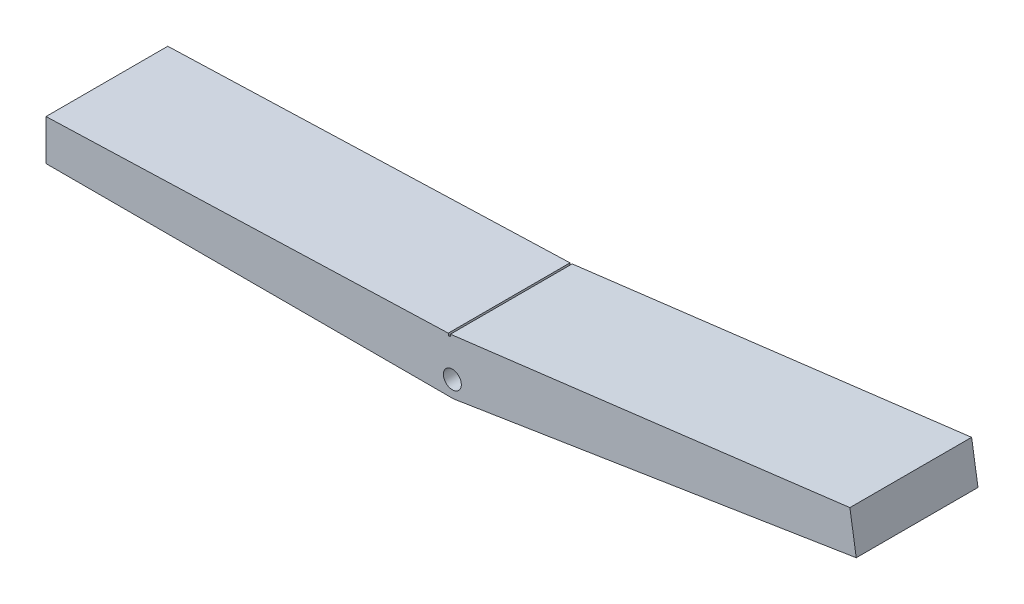
SolidWorks part; units mm, degrees
ref_plane "Front Plane" through (0, 0, 0) normal (0, 0, 1) x (1, 0, 0)
ref_plane "Top Plane" through (0, 0, 0) normal (0, 1, 0) x (1, 0, 0)
ref_plane "Right Plane" through (0, 0, 0) normal (1, 0, 0) x (0, 0, -1)
sketch "Sketch1" plane through (0, 0, 0) normal (0, 0, 1) x (1, 0, 0)
  line L1 (0, 0) -> (-75, 0)
  line L4 (-75, 0) -> (-75, 7.5)
  line L5 (0, 0) -> (5, 0) construction
  line L6 (0, 0) -> (74.0766, 11.7326)
  line L7 (74.0766, 11.7326) -> (72.9034, 19.1402)
  line L9 (74.0766, 0) -> (74.0766, 11.7326) construction
  line L10 (74.0766, 0) -> (0, 0) construction
  line L11 (-0.787, 10) -> (0, 0) construction
  line L12 (-0.787, 10) -> (-75, 7.5)
  line L13 (-0.787, 10) -> (72.9034, 19.1402)
  circle A0 centre (-0.2354, 2.9908) radius 1.65
  dimension "D8" = 3.3
  dimension "D3" = 75
  dimension "D4" = 75
  dimension "D5" = 5
  dimension "D7" = 3
  dimension "D6" = 9
  dimension "D9" = 85.5
extrude "Boss-Extrude1" add sketch "Sketch1" along normal blind 22.4 contours L4 L12 L13 L7 L6 L1 | A0
sketch "Sketch2" plane through (0, 0, 0) normal (0.1564, -0.9877, 0) x (0.9877, 0.1564, 0)
  line L0 (67, 7.7) -> (67, 14.7) construction
  line L1 (67, 11.2) -> (75, 11.2) construction
  line L2 (75, 22.4) -> (75, 0) construction
  circle A0 centre (67, 14.7) radius 3.05
  circle A1 centre (67, 7.7) radius 3.05
  dimension "D1" = 6.1
  dimension "D2" = 7
  dimension "D3" = 8
extrude "Cut-Extrude1" cut sketch "Sketch2" against normal blind 3
ref_plane "Plane1" through (0, 0, 0) normal (0.9969, 0.0785, 0) x (0, 0, -1)
mirror "Mirror1" about plane through (0, 0, 0) normal (0.9969, 0.0785, 0) of "Cut-Extrude1"
ref_plane "Plane2" through (-1.0483, 13.3201, 0) normal (-0.0785, 0.9969, 0) x (0.9969, 0.0785, 0)
sketch "Sketch3" plane through (-1.0483, 13.3201, 0) normal (-0.0785, 0.9969, 0) x (0.9969, 0.0785, 0)
  line L0 (0, 0) -> (74.1804, 0) construction
  line L1 (-0.2, 0) -> (0.2, 0)
  line L2 (-0.2, 0) -> (-0.2, -22.4)
  line L3 (-0.2, -22.4) -> (0.2, -22.4)
  line L4 (0.2, 0) -> (0.2, -22.4)
  line L5 (-0.2, 0) -> (0.2, -22.4) construction
  line L6 (-0.2, -22.4) -> (0.2, 0) construction
  point P0 (0, -11.2)
  point P5 (0, -22.4)
  dimension "D1" = 0.4
extrude "Cut-Extrude2" cut sketch "Sketch3" against normal offset from surface (3.7398 mm away) 0.4
equation "\"D4@Sketch1\"=\"D3@Sketch1\""
